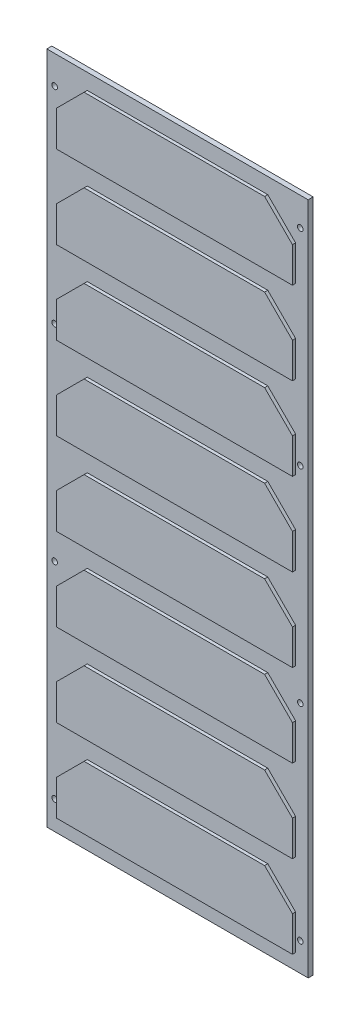
SolidWorks part; units mm, degrees
ref_plane "Front Plane" through (0, 0, 0) normal (0, 0, 1) x (1, 0, 0)
ref_plane "Top Plane" through (0, 0, 0) normal (0, 1, 0) x (1, 0, 0)
ref_plane "Right Plane" through (0, 0, 0) normal (1, 0, 0) x (0, 0, -1)
sketch "Sketch1" plane through (0, 0, 0) normal (0, 0, 1) x (1, 0, 0)
  line L1 (-41.5, -107) -> (41.5, -107)
  line L2 (-41.5, -107) -> (-41.5, 107)
  line L3 (-41.5, 107) -> (41.5, 107)
  line L4 (41.5, -107) -> (41.5, 107)
  line L5 (-41.5, -107) -> (41.5, 107) construction
  line L6 (-41.5, 107) -> (41.5, -107) construction
  point P0 (0, 0)
  dimension "D1" = 83
  dimension "D2" = 214
extrude "Boss-Extrude1" add sketch "Sketch1" along normal blind 1.5875
sketch "Sketch2" plane through (0, 0, 1.5875) normal (0, 0, 1) x (1, 0, 0)
  line L0 (-28.6612, 102) -> (28.6612, 102)
  line L1 (28.6612, 102) -> (37.5, 93.1612)
  line L2 (37.5, 93.1612) -> (37.5, 82)
  line L3 (37.5, 82) -> (-37.5, 82)
  line L4 (-37.5, 82) -> (-37.5, 93.1612)
  line L5 (-37.5, 93.1612) -> (-28.6612, 102)
  line L6 (0, 0) -> (0, 107) construction
  line L7 (41.5, 107) -> (-41.5, 107) construction
  line L8 (-28.6612, 75.7143) -> (28.6612, 75.7143)
  line L9 (28.6612, 75.7143) -> (37.5, 66.8755)
  line L10 (37.5, 66.8755) -> (37.5, 55.7143)
  line L11 (37.5, 55.7143) -> (-37.5, 55.7143)
  line L12 (-37.5, 55.7143) -> (-37.5, 66.8755)
  line L13 (-37.5, 66.8755) -> (-28.6612, 75.7143)
  line L14 (-28.6612, 49.4286) -> (28.6612, 49.4286)
  line L15 (28.6612, 49.4286) -> (37.5, 40.5897)
  line L16 (37.5, 40.5897) -> (37.5, 29.4286)
  line L17 (37.5, 29.4286) -> (-37.5, 29.4286)
  line L18 (-37.5, 29.4286) -> (-37.5, 40.5897)
  line L19 (-37.5, 40.5897) -> (-28.6612, 49.4286)
  line L20 (-28.6612, 23.1429) -> (28.6612, 23.1429)
  line L21 (28.6612, 23.1429) -> (37.5, 14.304)
  line L22 (37.5, 14.304) -> (37.5, 3.1429)
  line L23 (37.5, 3.1429) -> (-37.5, 3.1429)
  line L24 (-37.5, 3.1429) -> (-37.5, 14.304)
  line L25 (-37.5, 14.304) -> (-28.6612, 23.1429)
  line L26 (-28.6612, -3.1429) -> (28.6612, -3.1429)
  line L27 (28.6612, -3.1429) -> (37.5, -11.9817)
  line L28 (37.5, -11.9817) -> (37.5, -23.1429)
  line L29 (37.5, -23.1429) -> (-37.5, -23.1429)
  line L30 (-37.5, -23.1429) -> (-37.5, -11.9817)
  line L31 (-37.5, -11.9817) -> (-28.6612, -3.1429)
  line L32 (-28.6612, -29.4286) -> (28.6612, -29.4286)
  line L33 (28.6612, -29.4286) -> (37.5, -38.2674)
  line L34 (37.5, -38.2674) -> (37.5, -49.4286)
  line L35 (37.5, -49.4286) -> (-37.5, -49.4286)
  line L36 (-37.5, -49.4286) -> (-37.5, -38.2674)
  line L37 (-37.5, -38.2674) -> (-28.6612, -29.4286)
  line L38 (-28.6612, -55.7143) -> (28.6612, -55.7143)
  line L39 (28.6612, -55.7143) -> (37.5, -64.5531)
  line L40 (37.5, -64.5531) -> (37.5, -75.7143)
  line L41 (37.5, -75.7143) -> (-37.5, -75.7143)
  line L42 (-37.5, -75.7143) -> (-37.5, -64.5531)
  line L43 (-37.5, -64.5531) -> (-28.6612, -55.7143)
  line L44 (-28.6612, -82) -> (28.6612, -82)
  line L45 (28.6612, -82) -> (37.5, -90.8388)
  line L46 (37.5, -90.8388) -> (37.5, -102)
  line L47 (37.5, -102) -> (-37.5, -102)
  line L48 (-37.5, -102) -> (-37.5, -90.8388)
  line L49 (-37.5, -90.8388) -> (-28.6612, -82)
  line L50 (-41.5, -107) -> (41.5, -107) construction
  dimension "D1" = 75
  dimension "D2" = 20
  dimension "D3" = 45
  dimension "D4" = 12.5
  dimension "D5" = 5
  dimension "D7" = 5
  dimension "D6" = 8
extrude "Boss-Extrude2" add sketch "Sketch2" along normal blind 1
hole_wizard "#0 Clearance Hole1" positions "Sketch4" profile "Sketch3" hole size "#0" standard "ANSI Inch"
sketch "Sketch4" plane through (0, 0, 1.5875) normal (0, 0, 1) x (1, 0, 0)
  line L1 (-41.5, 107) -> (-41.5, -107) construction
  line L2 (41.5, -107) -> (41.5, 107) construction
  line L4 (-41.5, 0) -> (41.5, 0) construction
  line L6 (-39, 98) -> (-39, 32.6667) construction
  line L7 (-39, 32.6667) -> (-39, -32.6667) construction
  point P0 (-39, 98)
  point P2 (39, 98)
  point P4 (39, 32.6667)
  point P6 (39, -32.6667)
  point P8 (39, -98)
  point P10 (-39, -98)
  point P12 (-39, -32.6667)
  point P14 (-39, 32.6667)
  dimension "D1" = 196
  dimension "D2" = 2.5
  dimension "D3" = 2.5
sketch "Sketch3" plane through (-39, 98, 1.5875) normal (1, 0, 0) x (0, -1, 0)
  line L0 (0, 0) -> (0, 3.7092)
  line L1 (0, 3.7092) -> (0.889, 3.175)
  line L2 (0.889, 3.175) -> (0.889, 0)
  line L5 (0.889, 0) -> (0, 0)
  line L10 (0, 3.7092) -> (-0.889, 3.175) construction
  line L11 (0, -6.35) -> (0, 107.95) construction
  dimension "Hole Dia." = 1.778
  dimension "Hole Depth" = 3.175
  dimension "Drill Angle" = 118
